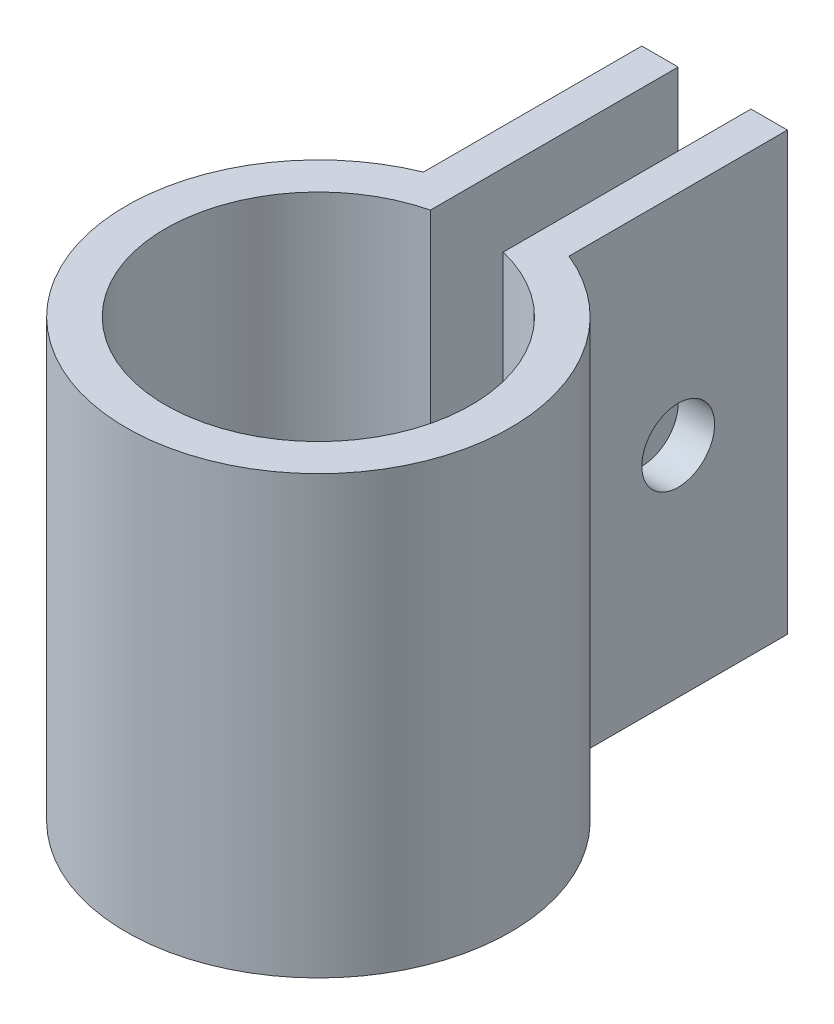
SolidWorks part; units mm, degrees
ref_plane "Front Plane" through (0, 0, 0) normal (0, 0, 1) x (1, 0, 0)
ref_plane "Top Plane" through (0, 0, 0) normal (0, 1, 0) x (1, 0, 0)
ref_plane "Right Plane" through (0, 0, 0) normal (1, 0, 0) x (0, 0, -1)
sketch "Sketch1" plane through (0, 0, 0) normal (0, 1, 0) x (1, 0, 0)
  circle A0 centre (0, 0) radius 13.335
  circle A1 centre (0, 0) radius 16.764
  dimension "D1" = 33.528
  dimension "D2" = 26.67
extrude "Boss-Extrude1" add sketch "Sketch1" along normal blind 38.1
sketch "Sketch2" plane through (0, 38.1, 0) normal (0, 1, 0) x (1, 0, 0)
  line L1 (-3.175, 12.9515) -> (3.175, 12.9515)
  line L2 (-3.175, 12.9515) -> (-3.175, 16.764)
  line L3 (-3.175, 16.764) -> (3.175, 16.764)
  line L4 (3.175, 12.9515) -> (3.175, 16.764)
  circle A0 centre (0, 0) radius 13.335 construction
  circle A1 centre (0, 0) radius 16.764 construction
  dimension "D1" = 6.35
extrude "Cut-Extrude1" cut sketch "Sketch2" against normal through all
sketch "Sketch3" plane through (0, 38.1, 0) normal (0, 1, 0) x (1, 0, 0)
  line L0 (-3.175, 16.4606) -> (-3.175, 12.9515) construction
  line L1 (-6.35, 15.5148) -> (-3.175, 15.5148)
  line L2 (-6.35, 15.5148) -> (-6.35, 34.5648)
  line L3 (-6.35, 34.5648) -> (-3.175, 34.5648)
  line L4 (-3.175, 15.5148) -> (-3.175, 34.5648)
  arc A0 (-3.175, 16.4606) -> (3.175, 16.4606) centre (0, 0) ccw construction
  dimension "D1" = 3.175
  dimension "D2" = 19.05
extrude "Boss-Extrude2" add sketch "Sketch3" against normal up to surface (38.1 mm away) up to face at (0, 0, 0.1717)
sketch "Sketch4" plane through (-6.35, 0, 0) normal (-1, 0, 0) x (0, 0, 1)
  line L0 (-15.5148, 0) -> (-34.5648, 38.1) construction
  circle A0 centre (-25.0398, 19.05) radius 3.175
  dimension "D1" = 6.35
extrude "Cut-Extrude2" cut sketch "Sketch4" against normal through all
mirror "Mirror1" about plane through (0, 0, 0) normal (1, 0, 0) of "Boss-Extrude2", "Cut-Extrude2"
